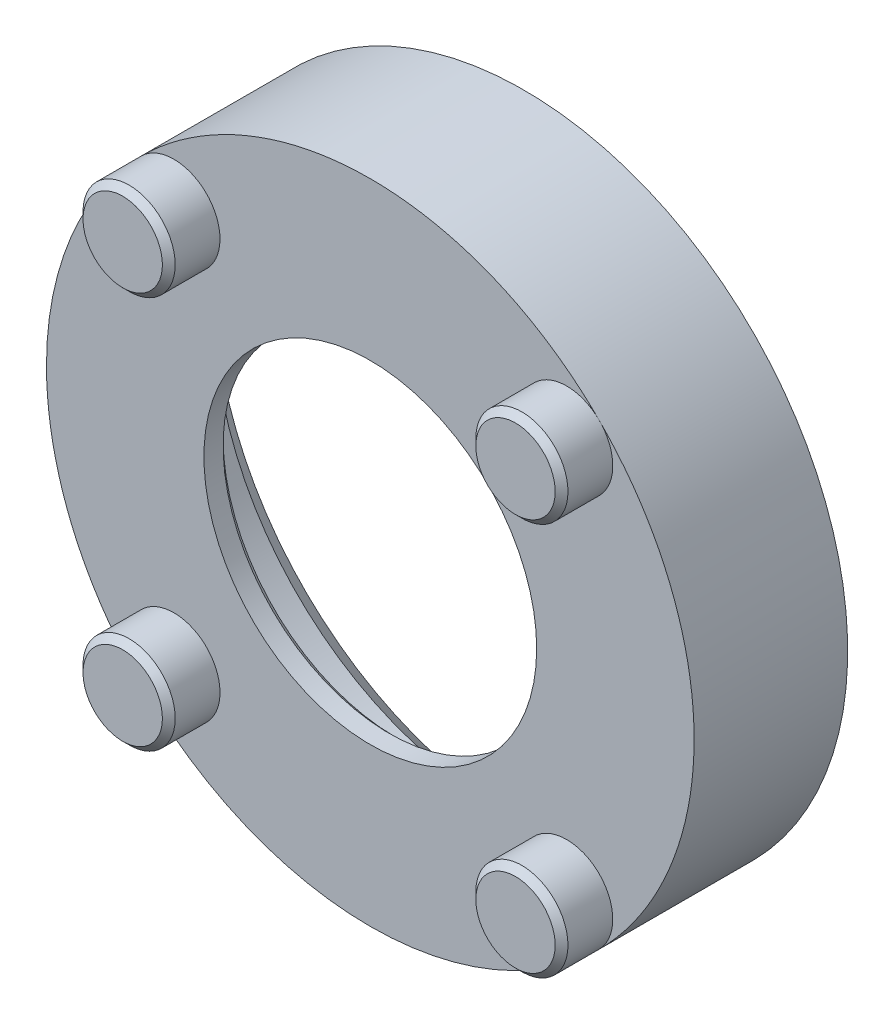
SolidWorks part; units mm, degrees
ref_plane "Front Plane" through (0, 0, 0) normal (0, 0, 1) x (1, 0, 0)
ref_plane "Top Plane" through (0, 0, 0) normal (0, 1, 0) x (1, 0, 0)
ref_plane "Right Plane" through (0, 0, 0) normal (1, 0, 0) x (0, 0, -1)
sketch "Sketch1" plane through (0, 0, 0) normal (0, 0, 1) x (1, 0, 0)
  circle A1 centre (0, 0) radius 12.6
  circle A2 centre (0, 0) radius 11.1
  circle A3 centre (0, 0) radius 11.1
  dimension "D1" = 0.1
  dimension "D2" = 1.5
extrude "Boss-Extrude1" add sketch "Sketch1" against normal blind 5
chamfer "Chamfer1" distance 1 angle 45 1 edges at (11.1, 0, -5)
sketch "Sketch2" plane through (0, 0, 0) normal (0, 0, 1) x (1, 0, 0)
  circle A5 centre (7.6721, -7.6721) radius 1.8
  circle A14 centre (-7.6721, -7.6721) radius 1.8
  circle A15 centre (-7.6721, 7.6721) radius 1.8
  circle A16 centre (7.6721, 7.6721) radius 1.8
  point P2 (0, 0)
  point P3 (0, 0)
  point P14 (0, 0)
  point P20 (0, 0)
  dimension "D2" = 4
  dimension "D1" = 3.6
extrude "Boss-Extrude2" add sketch "Sketch2" along normal blind 3
sketch "Sketch3" plane through (0, 0, 0) normal (0, 0, 1) x (1, 0, 0)
  circle A1 centre (0, 0) radius 12.6
extrude "Boss-Extrude3" add sketch "Sketch3" along normal blind 1
sketch "Sketch5" plane through (0, 0, 0) normal (0, 0, 1) x (1, 0, 0)
  circle A0 centre (0, 0) radius 6.5
  point P0 (0, 0)
  dimension "D1" = 13
extrude "Cut-Extrude1" cut sketch "Sketch5" along normal through all
chamfer "Chamfer2" distance 0.25 angle 45 4 edges at (-5.8721, 7.6721, 3) (9.4721, 7.6721, 3) (-5.8721, -7.6721, 3) (9.4721, -7.6721, 3)
sketch "Sketch6" plane through (0, 0, 3) normal (0, 0, 1) x (1, 0, 0)
  circle A0 centre (-7.6721, 7.6721) radius 0.675
  circle A1 centre (-7.6721, -7.6721) radius 0.675
  circle A2 centre (7.6721, -7.6721) radius 0.675
  circle A3 centre (7.6721, 7.6721) radius 0.675
  dimension "D1" = 1.35
extrude "Cut-Extrude2" [suppressed] cut sketch "Sketch6" against normal blind 4.5
chamfer "Chamfer3" distance 0.25 angle 45 1 edges at (6.5, 0, 0)
sketch "Sketch7" plane through (0, 0, -5) normal (0, 0, -1) x (-1, 0, 0)
  circle A0 centre (0, 0) radius 12.6
  circle A1 centre (0, 0) radius 12.65
extrude "Boss-Extrude4" add sketch "Sketch7" against normal up to surface (6 mm away) up to face at (6.5, 0, 1)
